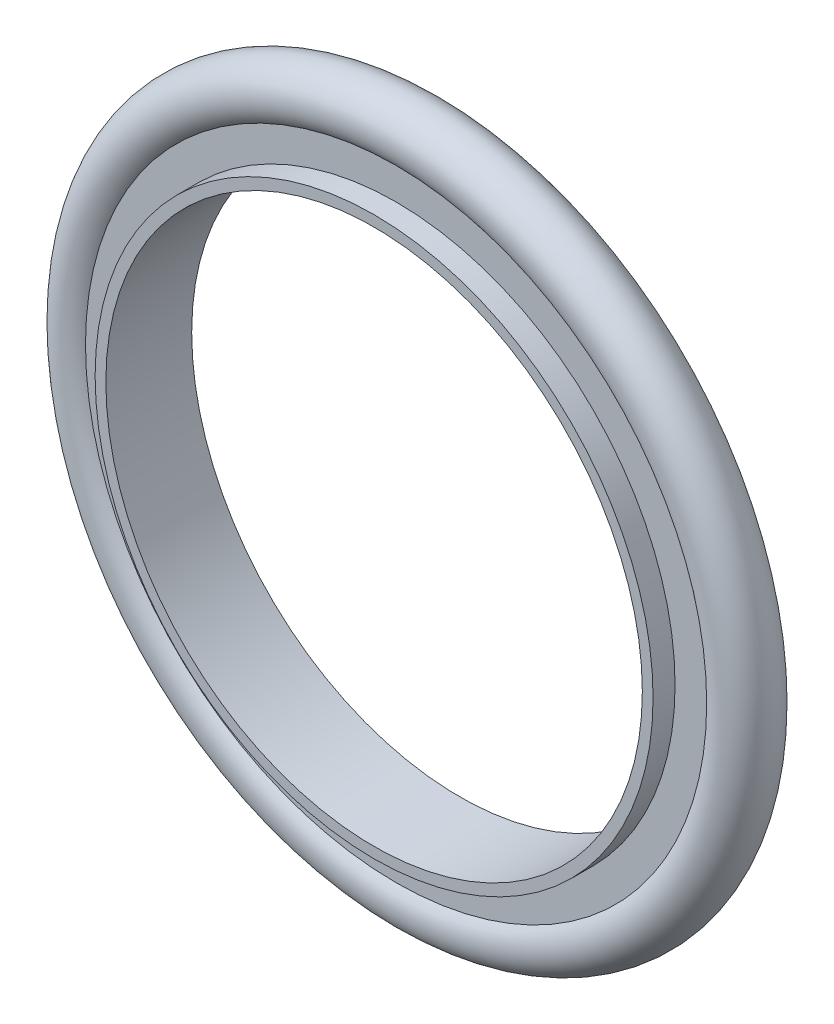
SolidWorks part; units mm, degrees
material "ASTM A36 Steel"
ref_plane "Front Plane" through (0, 0, 0) normal (0, 0, 1) x (1, 0, 0)
ref_plane "Top Plane" through (0, 0, 0) normal (0, 1, 0) x (1, 0, 0)
ref_plane "Right Plane" through (0, 0, 0) normal (1, 0, 0) x (0, 0, -1)
sketch "Sketch1" plane through (0, 0, 0) normal (1, 0, 0) x (0, 0, -1)
  line L0 (-4, 25) -> (4, 25)
  line L1 (4, 25) -> (4, 26)
  line L2 (4, 26) -> (1.95, 26)
  line L3 (1.95, 26) -> (1.95, 28.9475)
  line L4 (-4, 25) -> (-4, 26)
  line L5 (-4, 26) -> (-1.95, 26)
  line L6 (-1.95, 26) -> (-1.95, 28.9475)
  line L7 (6.8033, 0) -> (32.2587, 0) construction
  arc A0 (1.95, 28.9475) -> (-1.95, 28.9475) centre (0, 30.7419) ccw
  point P10 (0, 25)
  dimension "D4" = 2.65
  dimension "D6" = 61.4838
  dimension "D1" = 50
  dimension "D2" = 1
  dimension "D3" = 3.9
  dimension "D5" = 8
  dimension "D7" = 4.7419
  dimension "D8" = 52
revolve "Revolve1" add sketch "Sketch1" angle 360 about L7
